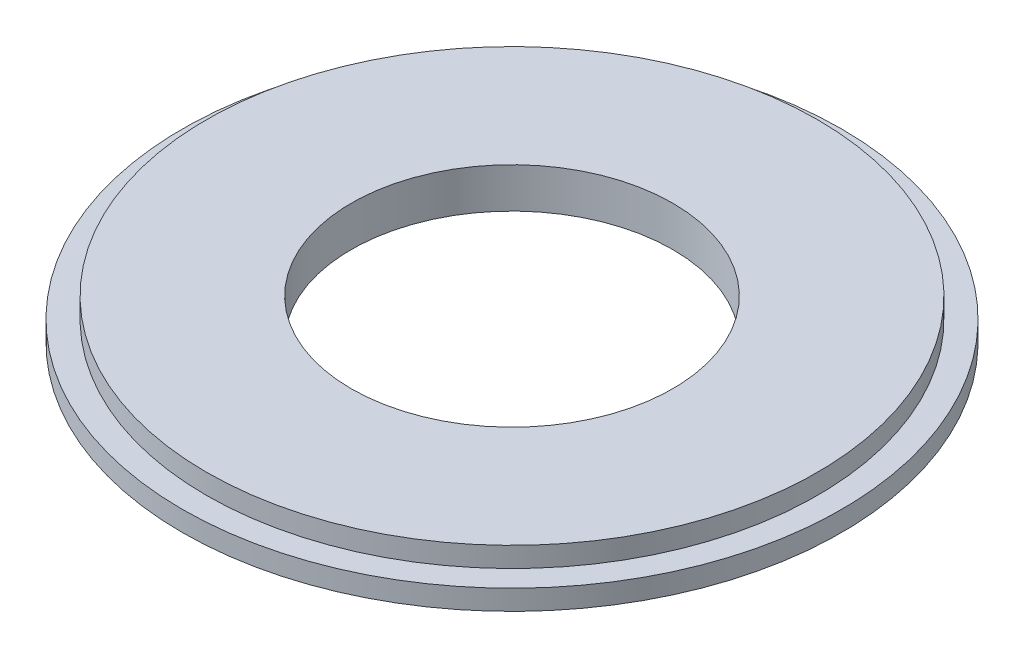
SolidWorks part; units mm, degrees
material "Balsa"
ref_plane "Front Plane" through (0, 0, 0) normal (0, 0, 1) x (1, 0, 0)
ref_plane "Top Plane" through (0, 0, 0) normal (0, 1, 0) x (1, 0, 0)
ref_plane "Right Plane" through (0, 0, 0) normal (1, 0, 0) x (0, 0, -1)
sketch "Sketch1" plane through (0, 0, 0) normal (0, 1, 0) x (1, 0, 0)
  arc A0 (-1.6184, 40.9521) -> (-40.968, 1.6024) centre (0, -0.016) ccw
  arc A2 (40.968, 1.6024) -> (1.6184, 40.9521) centre (0, -0.016) ccw
  arc A3 (1.6184, -40.984) -> (40.968, -1.6344) centre (0, -0.016) ccw
  arc A4 (-40.968, -1.6344) -> (-1.6184, -40.984) centre (0, -0.016) ccw
  circle A5 centre (0, -0.016) radius 41
  circle A6 centre (0, -0.016) radius 20
  point P4 (0, 40.984)
  point P19 (0, -0.016)
  dimension "D1" = 82
  dimension "D2" = 40
extrude "Boss-Extrude1" add sketch "Sketch1" along normal blind 2.5 contours A6 | A5
sketch "Sketch3" plane through (0, 2.5, 0) normal (0, 1, 0) x (1, 0, 0)
  circle A0 centre (0, -0.016) radius 38
  circle A1 centre (0, -0.016) radius 20 construction
  circle A2 centre (0, -0.016) radius 20
  dimension "D1" = 76
extrude "Boss-Extrude3" add sketch "Sketch3" along normal blind 2.5
